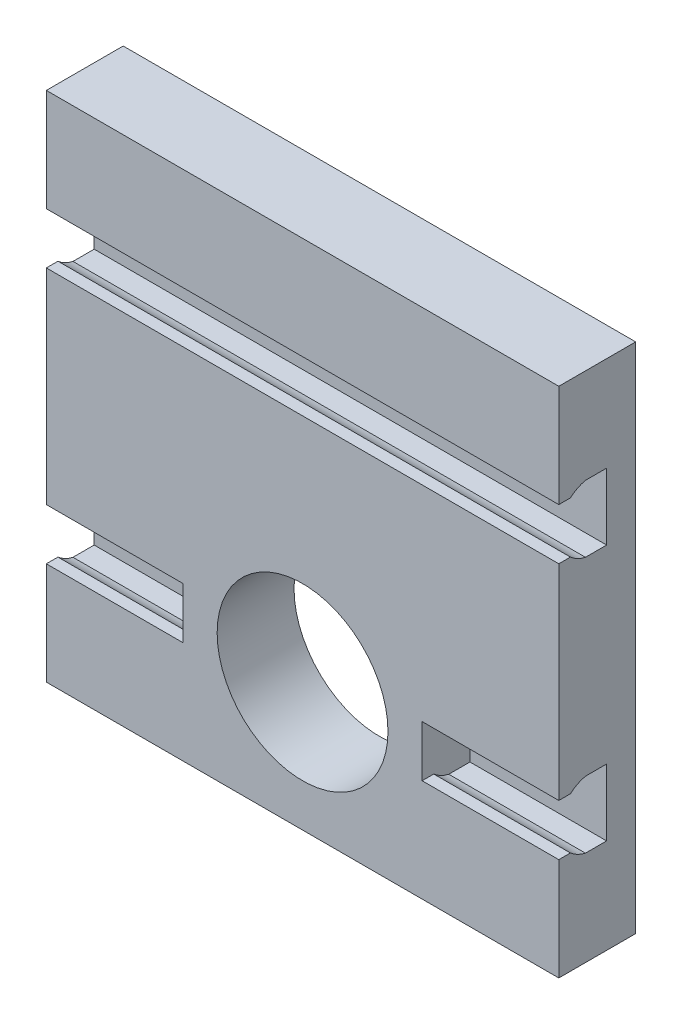
SolidWorks part; units mm, degrees
ref_plane "前视基准面" through (0, 0, 0) normal (0, 0, 1) x (1, 0, 0)
ref_plane "上视基准面" through (0, 0, 0) normal (0, 1, 0) x (1, 0, 0)
ref_plane "右视基准面" through (0, 0, 0) normal (1, 0, 0) x (0, 0, -1)
other "Configuration Table"
sketch "草图2" plane through (0, 0, 0) normal (0, 0, 1) x (1, 0, 0)
  line L0 (0, 16.5) -> (0, -13.5) construction
  line L2 (-15, -13.5) -> (15, -13.5)
  line L3 (-15, -13.5) -> (-15, 16.5)
  line L4 (-15, 16.5) -> (15, 16.5)
  line L5 (15, -13.5) -> (15, 16.5)
  line L6 (-15, -13.5) -> (15, 16.5) construction
  line L7 (-15, 16.5) -> (15, -13.5) construction
  circle A0 centre (0, -6) radius 5
  circle A1 centre (0, 0) radius 16.5 construction
  point P7 (0, 1.5)
  dimension "D3" = 10
  dimension "D1" = 30
  dimension "D2" = 30
extrude "凸台-拉伸1" add sketch "草图2" along normal blind 4.5
sketch "草图4" plane through (15, 0, 0) normal (1, 0, 0) x (0, 0, -1)
  line L0 (-4.5, 1.5) -> (0, 1.5) construction
  line L1 (-4.5, -13.5) -> (-4.5, 16.5) construction
  line L2 (0, -13.5) -> (0, 16.5) construction
  line L3 (-1.7, 10.8343) -> (-1.7, 7.1657) construction
  line L4 (-4.5, 7.5) -> (-3.82, 7.5)
  line L5 (-4.5, 7.5) -> (-4.5, 10.5)
  line L6 (-4.5, 10.5) -> (-3.82, 10.5)
  line L7 (-3.82, 7.5) -> (-3.82, 10.5) construction
  line L8 (-2.9415, 7.05) -> (-2.9415, 10.95) construction
  line L9 (-4.5, 16.5) -> (0, 16.5) construction
  line L10 (-2.9415, 10.95) -> (-1.7, 10.95)
  line L11 (-2.9415, 10.95) -> (-2.9415, 7.05) construction
  line L12 (-2.9415, 7.05) -> (-1.7, 7.05)
  line L13 (-1.7, 10.95) -> (-1.7, 7.05)
  arc A0 (-3.82, 7.5) -> (-2.9415, 7.05) centre (-2.4971, 9) ccw
  arc A1 (-3.82, 10.5) -> (-3.82, 7.5) centre (-2.4971, 9) ccw construction
  arc A2 (-2.0527, 10.95) -> (-2.9415, 10.95) centre (-2.4971, 9) ccw construction
  arc A3 (-2.9415, 10.95) -> (-3.82, 10.5) centre (-2.4971, 9) ccw
  arc A4 (-1.7, 10.8343) -> (-2.0527, 10.95) centre (-2.4971, 9) ccw construction
  arc A5 (-1.7, 7.1657) -> (-1.7, 10.8343) centre (-2.4971, 9) ccw construction
  arc A6 (-2.0527, 7.05) -> (-1.7, 7.1657) centre (-2.4971, 9) ccw construction
  arc A7 (-2.9415, 7.05) -> (-2.0527, 7.05) centre (-2.4971, 9) ccw construction
  dimension "D1" = 4
  dimension "D2" = 0.68
  dimension "D3" = 3
  dimension "D4" = 2.8
  dimension "D5" = 3.9
  dimension "D6" = 5.55
extrude "切除-拉伸1" cut sketch "草图4" against normal through all
sketch "草图5" plane through (15, 0, 0) normal (1, 0, 0) x (0, 0, -1)
  line L0 (0, 1.5) -> (-4.5, 1.5) construction
  line L1 (0, -13.5) -> (0, 16.5) construction
  line L2 (-4.5, -13.5) -> (-4.5, 7.5) construction
  line L3 (-1.7, -4.05) -> (-1.7, -7.95)
  line L4 (-2.9415, -4.05) -> (-1.7, -4.05)
  line L5 (-4.5, -4.5) -> (-3.82, -4.5)
  line L6 (-1.7, 10.95) -> (-2.9415, 10.95)
  line L7 (-3.82, 10.5) -> (-4.5, 10.5)
  line L8 (-4.5, 10.5) -> (-4.5, 7.5)
  line L9 (-4.5, 7.5) -> (-3.82, 7.5)
  line L10 (-2.9415, 7.05) -> (-1.7, 7.05)
  line L11 (-1.7, 7.05) -> (-1.7, 10.95)
  line L12 (-1.7, 10.95) -> (-2.9415, 10.95) construction
  line L13 (-3.82, 10.5) -> (-4.5, 10.5) construction
  line L14 (-4.5, 10.5) -> (-4.5, 7.5) construction
  line L15 (-4.5, 7.5) -> (-3.82, 7.5) construction
  line L16 (-2.9415, 7.05) -> (-1.7, 7.05) construction
  line L17 (-1.7, 7.05) -> (-1.7, 10.95) construction
  line L18 (-4.5, -7.5) -> (-4.5, -4.5)
  line L19 (-3.82, -7.5) -> (-4.5, -7.5)
  line L20 (-1.7, -7.95) -> (-2.9415, -7.95)
  arc A0 (-3.82, -4.5) -> (-2.9415, -4.05) centre (-2.4971, -6) cw
  arc A1 (-2.9415, -7.95) -> (-3.82, -7.5) centre (-2.4971, -6) cw
  arc A2 (-2.9415, 10.95) -> (-3.82, 10.5) centre (-2.4971, 9) ccw
  arc A3 (-3.82, 7.5) -> (-2.9415, 7.05) centre (-2.4971, 9) ccw
  arc A4 (-2.9415, 10.95) -> (-3.82, 10.5) centre (-2.4971, 9) ccw construction
  arc A5 (-3.82, 7.5) -> (-2.9415, 7.05) centre (-2.4971, 9) ccw construction
  dimension "D1" = 0
extrude "切除-拉伸2" cut sketch "草图5" against normal blind 8
ref_plane "基准面1" through (0, 0, 0) normal (1, 0, 0) x (0, 0, -1)
mirror "镜向1" about plane through (0, 0, 0) normal (1, 0, 0) of "切除-拉伸2"
